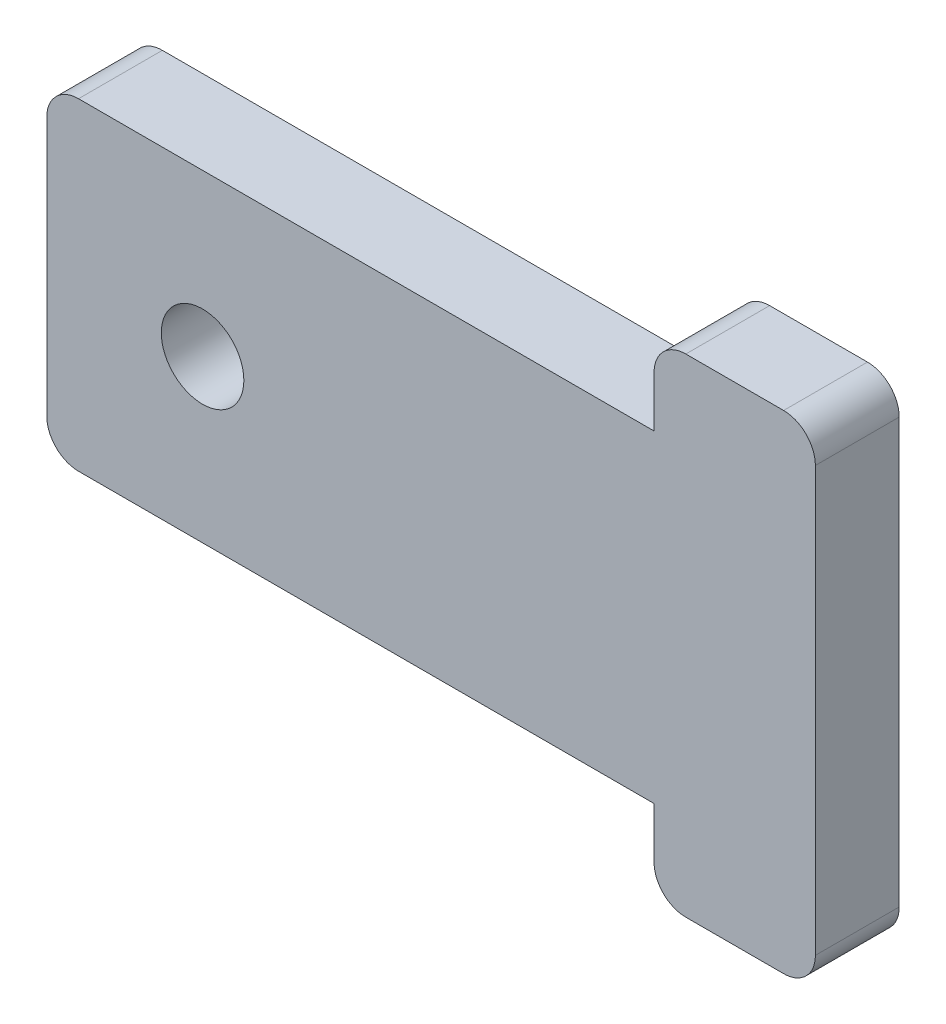
SolidWorks part; units mm, degrees
ref_plane "Front Plane" through (0, 0, 0) normal (0, 0, 1) x (1, 0, 0)
ref_plane "Top Plane" through (0, 0, 0) normal (0, 1, 0) x (1, 0, 0)
ref_plane "Right Plane" through (0, 0, 0) normal (1, 0, 0) x (0, 0, -1)
sketch "Model" plane through (0, 0, 0) normal (0, 0, 1) x (1, 0, 0)
  line L0 (58.01, 31.9) -> (50.31, 31.9)
  line L1 (60.51, -4) -> (60.51, 29.4)
  line L2 (50.31, -6.5) -> (58.01, -6.5)
  line L3 (47.81, 0) -> (47.81, -4)
  line L4 (2.5, 0) -> (47.81, 0)
  line L5 (0, 22.9) -> (0, 2.5)
  line L6 (47.81, 25.4) -> (2.5, 25.4)
  line L7 (47.81, 29.4) -> (47.81, 25.4)
  circle A0 centre (12.2648, 12.7) radius 3.25
  arc A1 (2.5, 25.4) -> (0, 22.9) centre (2.5, 22.9) ccw
  arc A2 (50.31, 31.9) -> (47.81, 29.4) centre (50.31, 29.4) ccw
  arc A3 (60.51, 29.4) -> (58.01, 31.9) centre (58.01, 29.4) ccw
  arc A4 (58.01, -6.5) -> (60.51, -4) centre (58.01, -4) ccw
  arc A5 (47.81, -4) -> (50.31, -6.5) centre (50.31, -4) ccw
  arc A6 (0, 2.5) -> (2.5, 0) centre (2.5, 2.5) ccw
extrude "Boss-Extrude1" add sketch "Model" along normal blind 6.6
